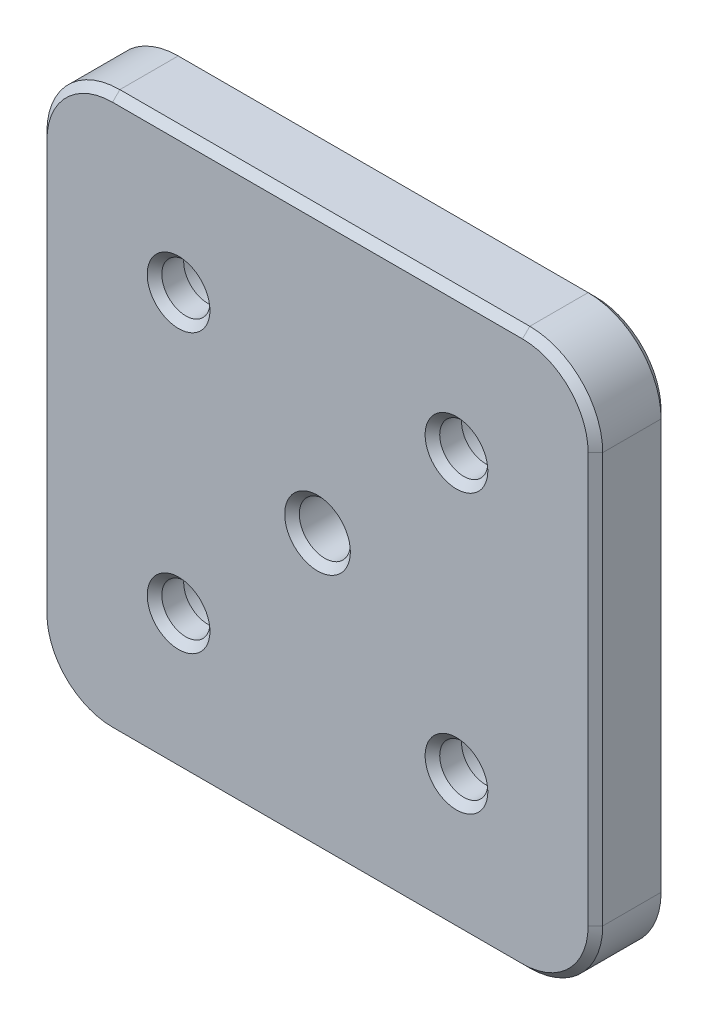
SolidWorks part; units mm, degrees
ref_plane "Front Plane" through (0, 0, 0) normal (0, 0, 1) x (1, 0, 0)
ref_plane "Top Plane" through (0, 0, 0) normal (0, 1, 0) x (1, 0, 0)
ref_plane "Right Plane" through (0, 0, 0) normal (1, 0, 0) x (0, 0, -1)
sketch "Sketch1" plane through (0, 0, 0) normal (0, 0, 1) x (1, 0, 0)
  circle A0 centre (0, 0) radius 7.5
sketch "Sketch3" plane through (0, 0, 0) normal (0, 0, 1) x (1, 0, 0)
  line L1 (-38.1, 38.1) -> (38.1, 38.1)
  line L2 (-38.1, 38.1) -> (-38.1, -38.1)
  line L3 (-38.1, -38.1) -> (38.1, -38.1)
  line L4 (38.1, 38.1) -> (38.1, -38.1)
  line L5 (-38.1, 38.1) -> (38.1, -38.1) construction
  line L6 (-38.1, -38.1) -> (38.1, 38.1) construction
  point P0 (0, 0)
extrude "Boss-Extrude3" add sketch "Sketch3" along normal blind 10
sketch "Sketch2" plane through (0, 0, 0) normal (0, 0, -1) x (-1, 0, 0)
  circle A0 centre (0, 0) radius 10
sketch "Sketch4" plane through (0, 0, 0) normal (0, 0, 1) x (1, 0, 0)
  circle A0 centre (19.05, 19.05) radius 4
  circle A1 centre (-19.05, 19.05) radius 4
  circle A2 centre (-19.05, -19.05) radius 4
  circle A3 centre (19.05, -19.05) radius 4
  dimension "D1" = 2
  dimension "D2" = 2
hole_wizard "CBORE for M6 Hex Socket Head Cap1" positions "Sketch7" profile "Sketch8" counterbore size "M6" standard "BSI" end condition through all
sketch "Sketch7" plane through (0, 0, 0) normal (0, 0, -1) x (-1, 0, 0)
  point P0 (19.05, 19.05)
  point P3 (19.05, -19.05)
  point P6 (-19.05, 19.05)
  point P9 (-19.05, -19.05)
sketch "Sketch8" plane through (-19.05, 19.05, 0) normal (1, 0, 0) x (0, 1, 0)
  line L0 (0, 0) -> (0, 10)
  line L1 (0, 10) -> (3.3, 10)
  line L3 (3.3, 10) -> (3.3, 6)
  line L4 (3.3, 6) -> (5.5, 6)
  line L5 (5.5, 6) -> (5.5, 0)
  line L7 (5.5, 0) -> (0, 0)
  line L11 (0, -6.35) -> (0, 107.95) construction
  dimension "Thru Hole Dia." = 6.6
  dimension "Thru Hole Depth" = 10
  dimension "C'Bore Dia." = 11
  dimension "C'Bore Depth" = 6
fillet "Fillet1" radius 10 4 edges at (38.1, 38.1, 5) (38.1, -38.1, 5) (-38.1, -38.1, 5) (-38.1, 38.1, 5)
extrude "Boss-Extrude4" add sketch "Sketch2" along normal blind 10
sketch "Sketch9" plane through (0, 0, -10) normal (0, 0, -1) x (-1, 0, 0)
  circle A0 centre (0, 0) radius 3.5
extrude "Cut-Extrude1" cut sketch "Sketch9" against normal through all
chamfer "Chamfer1" distance 1 angle 45 27 edges at (35.1711, -35.1711, 10) (0, -38.1, 10) (-35.1711, -35.1711, 10) (-38.1, 0, 10) (-35.1711, 35.1711, 10) (0, 38.1, 10) (35.1711, 35.1711, 10) (38.1, 0, 10) (15.75, -19.05, 10) (15.75, 19.05, 10) (-22.35, -19.05, 10) (-22.35, 19.05, 10) (-3.5, 0, 10) (-3.5, 0, -10) (-10, 0, -10) (13.55, 19.05, 0) (13.55, -19.05, 0) (-24.55, -19.05, 0) (-24.55, 19.05, 0) (38.1, 0, 0) (35.1711, 35.1711, 0) (35.1711, -35.1711, 0) (0, 38.1, 0) (0, -38.1, 0) (-35.1711, 35.1711, 0) (-35.1711, -35.1711, 0) (-38.1, 0, 0)
